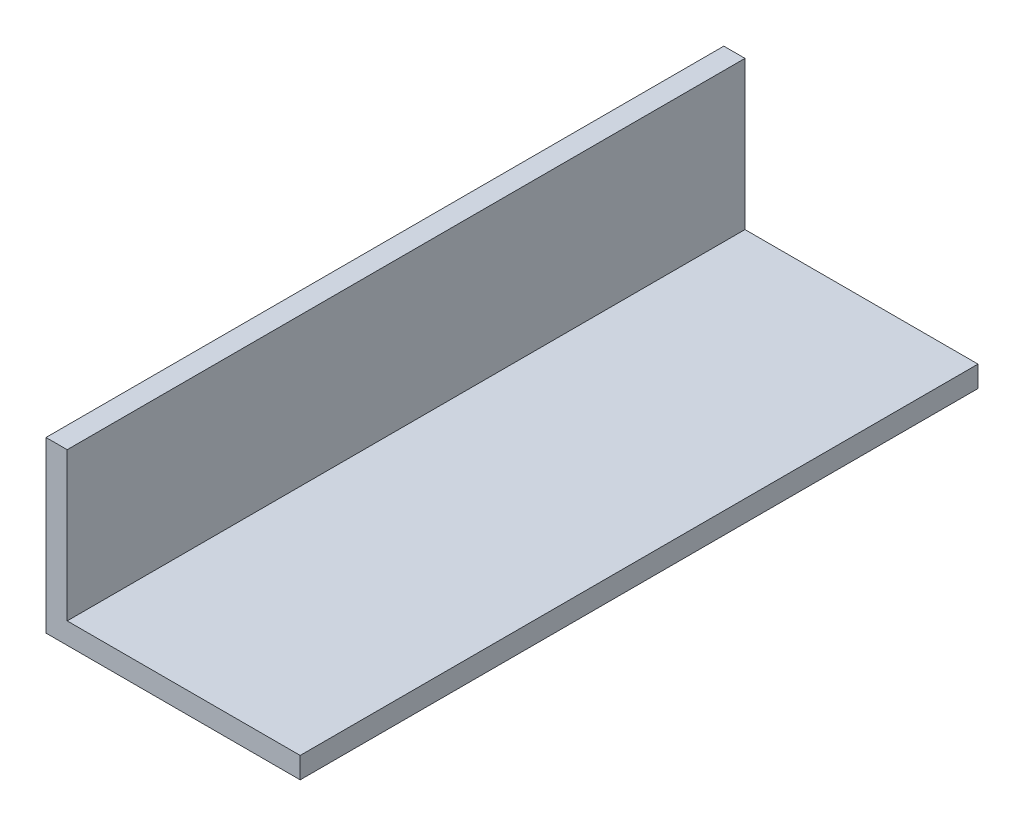
SolidWorks part; units mm, degrees
ref_plane "Front Plane" through (0, 0, 0) normal (0, 0, 1) x (1, 0, 0)
ref_plane "Top Plane" through (0, 0, 0) normal (0, 1, 0) x (1, 0, 0)
ref_plane "Right Plane" through (0, 0, 0) normal (1, 0, 0) x (0, 0, -1)
sketch "Sketch3" plane through (0, 0, 0) normal (0, 0, 1) x (1, 0, 0)
  line L0 (0, 0) -> (19.05, 0)
  line L1 (19.05, 0) -> (19.05, 1.5875)
  line L2 (19.05, 1.5875) -> (1.5875, 1.5875)
  line L3 (1.5875, 1.5875) -> (1.5875, 12.7)
  line L4 (1.5875, 12.7) -> (0, 12.7)
  line L5 (0, 12.7) -> (0, 0)
  dimension "D1" = 19.05
  dimension "D2" = 12.7
  dimension "D3" = 1.5875
  dimension "D4" = 1.5875
extrude "Boss-Extrude1" add sketch "Sketch3" along normal blind 50.8
sketch "Sketch4" plane through (1.5875, 0, 0) normal (1, 0, 0) x (0, 0, -1)
  line L0 (-50.8, 1.5875) -> (0, 1.5875) construction
  line L1 (-38.1, 1.5875) -> (-12.7, 1.5875)
  line L2 (-38.1, 1.5875) -> (-38.1, 5.3975)
  line L3 (-38.1, 5.3975) -> (-12.7, 5.3975)
  line L4 (-12.7, 1.5875) -> (-12.7, 5.3975)
  line L5 (-50.8, 12.7) -> (0, 12.7) construction
  point P8 (-25.4, 12.7)
  point P9 (-25.4, 5.3975)
  dimension "D1" = 25.4
  dimension "D2" = 3.81
extrude "Cut-Extrude1" [suppressed] cut sketch "Sketch4" against normal blind 2.54
